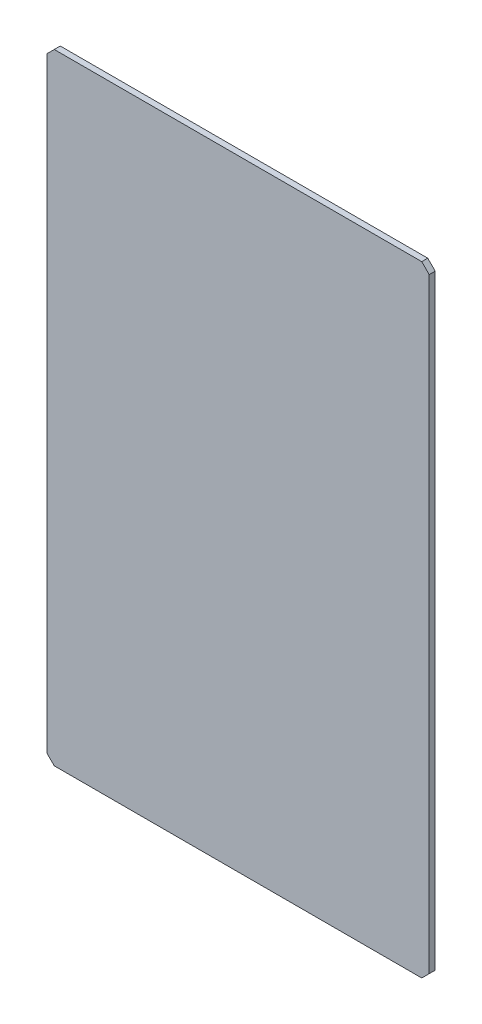
SolidWorks part; units mm, degrees
ref_plane "前视基准面" through (0, 0, 0) normal (0, 0, 1) x (1, 0, 0)
ref_plane "上视基准面" through (0, 0, 0) normal (0, 1, 0) x (1, 0, 0)
ref_plane "右视基准面" through (0, 0, 0) normal (1, 0, 0) x (0, 0, -1)
sketch "草图1" plane through (0, 0, 0) normal (0, 0, 1) x (1, 0, 0)
  line L2 (-28.2996, 98.6731) -> (-28.2996, -25.4144)
  line L3 (-28.2996, -25.4144) -> (48.2004, -25.4144)
  line L4 (48.2004, 98.6731) -> (48.2004, -25.4144)
  line L5 (-28.2996, 98.6731) -> (48.2004, 98.6731)
  line L7 (-26.2996, 99.1731) -> (46.2004, 99.1731) construction
  point P1 (0, 0)
  dimension "D1" = 76.5
  dimension "D2" = 0.5
extrude "凸台-拉伸1" add sketch "草图1" along normal blind 1.2
chamfer "倒角1" distance 1.5 angle 45 4 edges at (-28.2996, -25.4144, 0.6) (48.2004, -25.4144, 0.6) (48.2004, 98.6731, 0.6) (-28.2996, 98.6731, 0.6)
